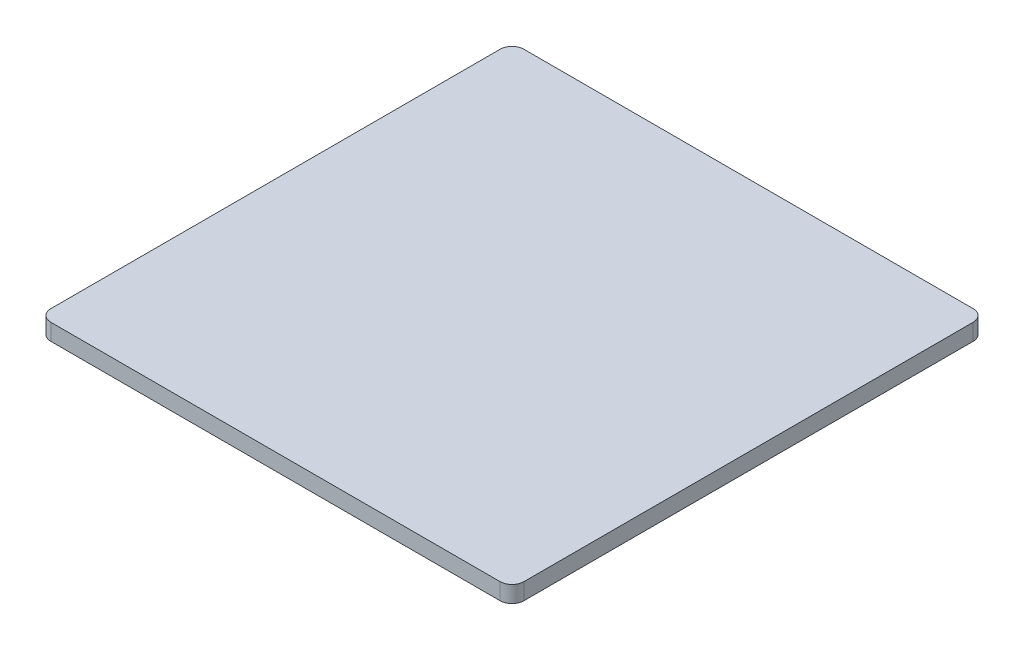
SolidWorks part; units mm, degrees
ref_plane "Front Plane" through (0, 0, 0) normal (0, 0, 1) x (1, 0, 0)
ref_plane "Top Plane" through (0, 0, 0) normal (0, 1, 0) x (1, 0, 0)
ref_plane "Right Plane" through (0, 0, 0) normal (1, 0, 0) x (0, 0, -1)
sketch "Sketch1" plane through (0, 0, 0) normal (0, 1, 0) x (1, 0, 0)
  line L0 (10, -9.5) -> (10, 9.5)
  line L1 (9.5, -10) -> (-9.5, -10)
  line L2 (9.5, 10) -> (-9.5, 10)
  line L3 (-10, -9.5) -> (-10, 9.5)
  line L4 (10, -10) -> (-10, 10) construction
  line L5 (10, 10) -> (-10, -10) construction
  arc A0 (10, 9.5) -> (9.5, 10) centre (9.5, 9.5) ccw
  arc A1 (9.5, -10) -> (10, -9.5) centre (9.5, -9.5) ccw
  arc A2 (-9.5, -10) -> (-10, -9.5) centre (-9.5, -9.5) cw
  arc A3 (-9.5, 10) -> (-10, 9.5) centre (-9.5, 9.5) ccw
  point P1 (0, 0)
  dimension "D3" = 0.5
  dimension "D1" = 20
  dimension "D2" = 20
extrude "Boss-Extrude1" add sketch "Sketch1" along normal blind 0.7
